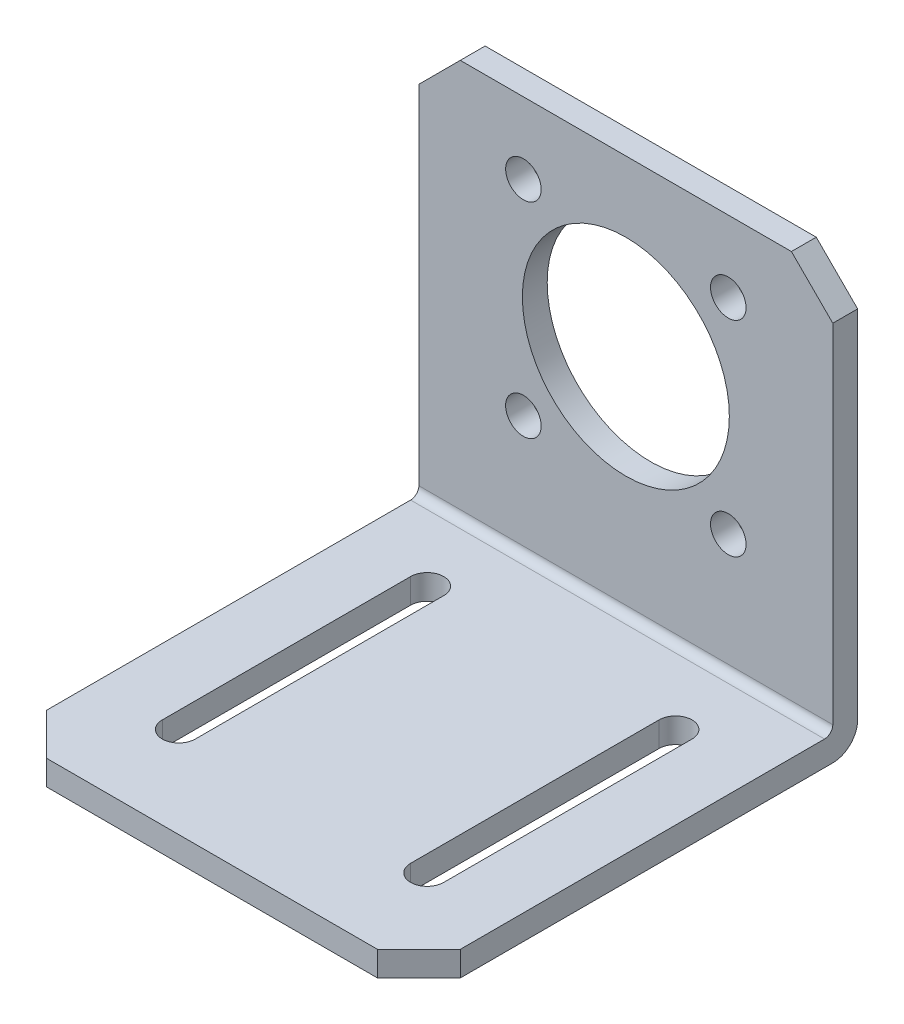
SolidWorks part; units mm, degrees
ref_plane "정면" through (0, 0, 0) normal (0, 0, 1) x (1, 0, 0)
ref_plane "윗면" through (0, 0, 0) normal (0, 1, 0) x (1, 0, 0)
ref_plane "우측면" through (0, 0, 0) normal (1, 0, 0) x (0, 0, -1)
sketch "스케치1" plane through (0, 0, 0) normal (1, 0, 0) x (0, 0, -1)
  line L0 (-18.5685, -10.3553) -> (31.4315, -10.3553)
  line L1 (34.4315, -7.3553) -> (34.4315, 40.6447)
  line L2 (-18.5685, -7.3553) -> (31.4315, -7.3553)
  line L3 (31.4315, -7.3553) -> (31.4315, 40.6447)
  line L4 (-18.5685, -10.3553) -> (-18.5685, -7.3553)
  line L5 (34.4315, 40.6447) -> (31.4315, 40.6447)
  arc A0 (31.4315, -10.3553) -> (34.4315, -7.3553) centre (31.4315, -7.3553) ccw
  arc A1 (31.4315, -7.3553) -> (31.4315, -7.3553) centre (31.4315, -7.3553) ccw
  point P5 (34.4315, -10.3553)
  dimension "D3" = 3
  dimension "D1" = 51
  dimension "D2" = 53
  dimension "D4" = 3
extrude "보스-돌출1" add sketch "스케치1" along normal blind 50
chamfer "모따기1" distance 5 angle 45 4 edges at (50, -8.8553, 18.5685) (0, -8.8553, 18.5685) (0, 40.6447, -32.9315) (50, 40.6447, -32.9315)
fillet "필렛1" radius 1 1 edges at (25, -7.3553, -31.4315)
sketch "스케치2" plane through (0, 0, -34.4315) normal (0, 0, -1) x (-1, 0, 0)
  line L0 (-25, -7.3553) -> (-25, 38.3346) construction
  line L1 (-50, -7.3553) -> (0, -7.3553) construction
  line L2 (-41.9486, 19.6447) -> (-7.7897, 19.6447) construction
  line L3 (-50, -10.3553) -> (0, -10.3553) construction
  line L4 (-25, 19.6447) -> (-40.226, 34.8707) construction
  circle A0 centre (-25, 19.6447) radius 12.5
  circle A1 centre (-37.3744, 32.019) radius 2.1478
  circle A2 centre (-12.6256, 32.019) radius 2.1478
  circle A3 centre (-12.6256, 7.2703) radius 2.1478
  circle A4 centre (-37.3744, 7.2703) radius 2.1478
  dimension "D2" = 17.5
  dimension "D1" = 30
extrude "컷-돌출1" cut sketch "스케치2" against normal through all
sketch "스케치3" plane through (0, -10.3553, 0) normal (0, -1, 0) x (1, 0, 0)
  line L0 (50, -34.4315) -> (0, -34.4315) construction
  line L1 (0, 13.5685) -> (0, -31.4315) construction
  line L2 (50, 13.5685) -> (50, -31.4315) construction
  line L3 (12, 7.5685) -> (12, -22.4315)
  line L4 (8, 7.5685) -> (8, -22.4315)
  line L5 (42, 7.5685) -> (42, -22.4315)
  line L6 (38, 7.5685) -> (38, -22.4315)
  arc A0 (12, 7.5685) -> (8, 7.5685) centre (10, 7.5685) ccw
  arc A1 (42, 7.5685) -> (38, 7.5685) centre (40, 7.5685) ccw
  arc A2 (8, -22.4315) -> (12, -22.4315) centre (10, -22.4315) ccw
  arc A3 (38, -22.4315) -> (42, -22.4315) centre (40, -22.4315) ccw
  dimension "D1" = 12
  dimension "D2" = 12
  dimension "D3" = 10
  dimension "D4" = 10
  dimension "D5" = 10
  dimension "D6" = 10
  dimension "D7" = 30
  dimension "D8" = 30
extrude "컷-돌출2" cut sketch "스케치3" against normal through all
